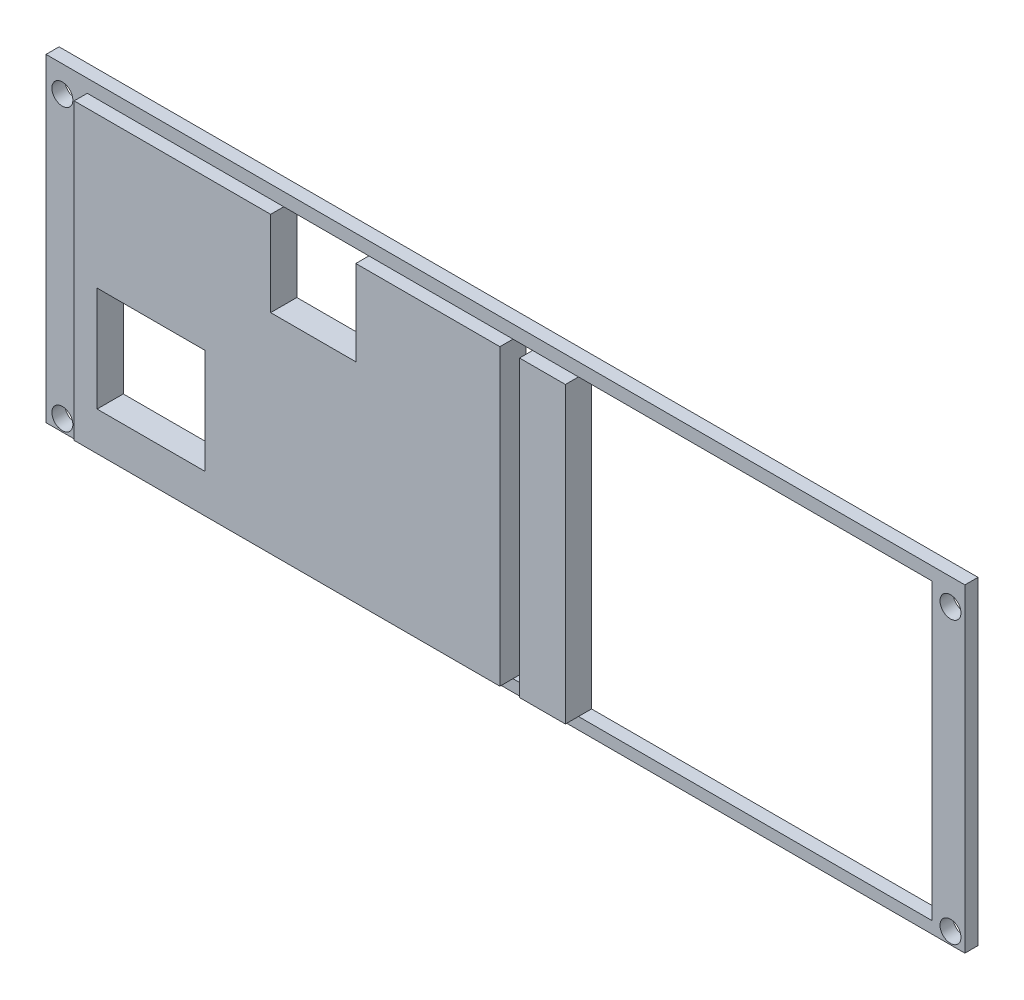
SolidWorks part; units mm, degrees
ref_plane "前视基准面" through (0, 0, 0) normal (0, 0, 1) x (1, 0, 0)
ref_plane "上视基准面" through (0, 0, 0) normal (0, 1, 0) x (1, 0, 0)
ref_plane "右视基准面" through (0, 0, 0) normal (1, 0, 0) x (0, 0, -1)
sketch "草图2" plane through (0, 0, 0) normal (0, 0, 1) x (1, 0, 0)
  line L1 (0, 0) -> (140.3, 0)
  line L2 (0, 0) -> (0, 48.7)
  line L3 (0, 48.7) -> (140.3, 48.7)
  line L4 (140.3, 0) -> (140.3, 48.7)
  dimension "D1" = 140.3
  dimension "D2" = 48.7
extrude "凸台-拉伸1" add sketch "草图2" along normal blind 4
sketch "草图3" plane through (0, 0, 4) normal (0, 0, 1) x (1, 0, 0)
  line L0 (140.3, 48.7) -> (0, 48.7) construction
  line L1 (6.3, 1.8) -> (135.3, 1.8)
  line L2 (6.3, 1.8) -> (6.3, 46.7)
  line L3 (6.3, 46.7) -> (135.3, 46.7)
  line L4 (135.3, 1.8) -> (135.3, 46.7)
  line L6 (140.3, 0) -> (140.3, 48.7) construction
  line L7 (2.5, 1.8) -> (6.3, 1.8) construction
  line L8 (135.3, 1.8) -> (138.1, 1.8) construction
  circle A0 centre (2.5, 44.7) radius 1.6
  circle A1 centre (2.5, 1.8) radius 1.6
  circle A2 centre (138.1, 44.7) radius 1.6
  circle A3 centre (138.1, 1.8) radius 1.6
  line M6 (0, 48.7) -> (0, 0)
  line M7 (0, 0) -> (140.3, 0)
  line M8 (140.3, 0) -> (140.3, 48.7)
  line M9 (140.3, 48.7) -> (0, 48.7)
  dimension "D10" = 2.8
  dimension "D1" = 129
  dimension "D2" = 44.9
  dimension "D3" = 2
  dimension "D4" = 5
  dimension "D5" = 2
  dimension "D6" = 3.8
  dimension "D7" = 3.8
  dimension "D8" = 2
  dimension "D9" = 2.8
extrude "切除-拉伸1" cut sketch "草图3" against normal blind 2 contours A3 A2 A1 A0 L4 L1 L2 L3 M9 M6 M7 M8
sketch "草图6" plane through (0, 0, 4) normal (0, 0, 1) x (1, 0, 0)
  line L0 (135.3, 1.8) -> (135.3, 46.7) construction
  line L1 (6.3, 46.7) -> (135.3, 46.7) construction
  line L2 (6.3, 1.8) -> (135.3, 1.8) construction
  line L3 (6.3, 1.8) -> (6.3, 46.7) construction
  line L4 (135.3, 1.8) -> (135.3, 46.7)
  line L5 (6.3, 46.7) -> (135.3, 46.7)
  line L6 (6.3, 1.8) -> (135.3, 1.8)
  line L7 (6.3, 1.8) -> (6.3, 46.7)
  line L8 (81.3, 46.7) -> (81.3, 1.8)
  line L9 (74.3, 46.7) -> (74.3, 1.8)
  line L10 (71.3, 46.7) -> (71.3, 1.8)
  line L11 (49.3, 46.7) -> (49.3, 33.7)
  line L12 (49.3, 33.7) -> (36.3, 33.7)
  line L13 (36.3, 33.7) -> (36.3, 46.7)
  line L15 (26.3, 23.7) -> (16.3, 23.7)
  line L16 (26.3, 23.7) -> (26.3, 7.7)
  line L17 (26.3, 7.7) -> (16.3, 7.7)
  line L18 (16.3, 23.7) -> (16.3, 7.7)
  circle A0 centre (138.1, 1.8) radius 1.6 construction
  circle A1 centre (138.1, 44.7) radius 1.6 construction
  circle A2 centre (2.5, 1.8) radius 1.6 construction
  circle A3 centre (2.5, 44.7) radius 1.6 construction
  circle A4 centre (138.1, 1.8) radius 1.6
  circle A5 centre (138.1, 44.7) radius 1.6
  circle A6 centre (2.5, 1.8) radius 1.6
  circle A7 centre (2.5, 44.7) radius 1.6
  line M1 (135.3, 1.8) -> (135.3, 46.7)
  line M2 (135.3, 46.7) -> (6.3, 46.7)
  dimension "D1" = 54
  dimension "D2" = 7
  dimension "D3" = 3
  dimension "D4" = 22
  dimension "D5" = 13
  dimension "D6" = 13
  dimension "D7" = 10
  dimension "D8" = 10
  dimension "D9" = 23
  dimension "D10" = 16
extrude "切除-拉伸2" cut sketch "草图6" against normal through all contours L8 L6 M2 M1 | L10 L6 L9 M2 | L13 L12 L11 M2 | L15 L18 L17 L16 | A7 | A6 | A5 | A4
sketch "草图7" plane through (0, 0, 0) normal (0, 0, -1) x (-1, 0, 0)
  line L2 (-16.3, 23.7) -> (-9.8, 23.7)
  line L3 (-9.8, 23.7) -> (-9.8, 7.7)
  line L4 (-9.8, 7.7) -> (-16.3, 7.7)
  line L5 (-16.3, 23.7) -> (-16.3, 7.7) construction
  line M9 (-16.3, 23.7) -> (-16.3, 7.7)
extrude "切除-拉伸3" cut sketch "草图7" against normal blind 10 and the other way through all contours L4 L3 L2 M9
